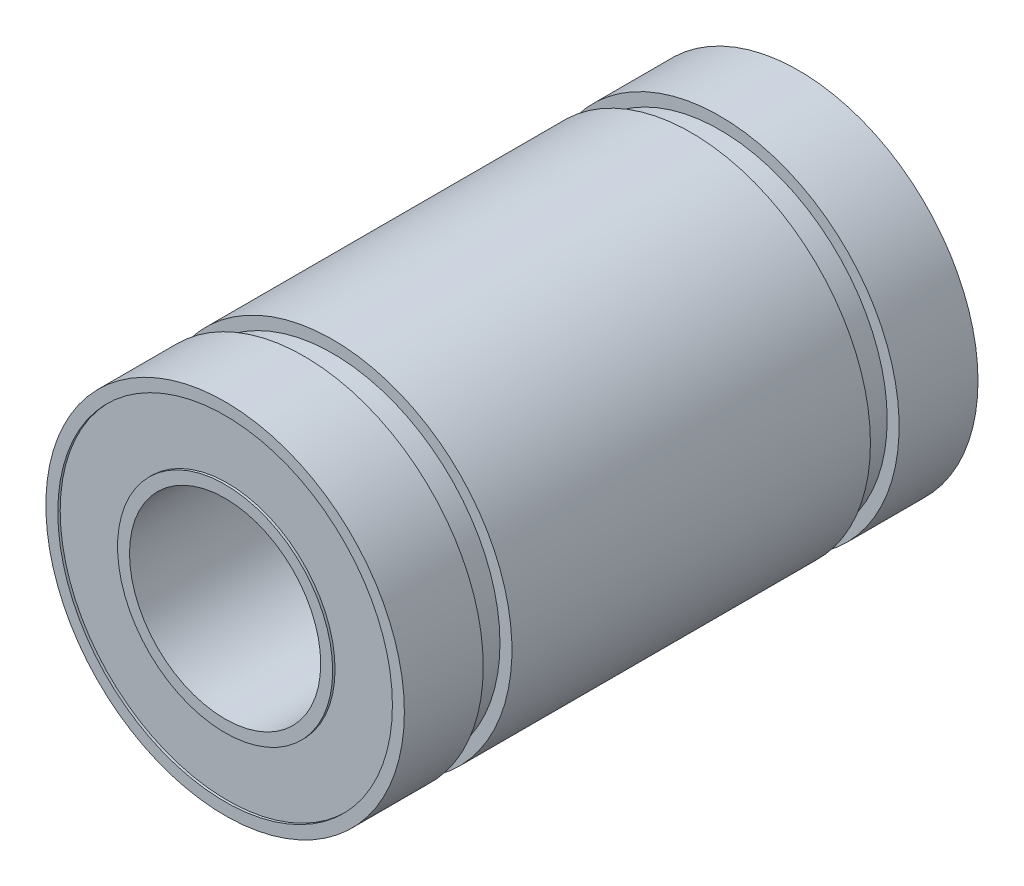
SolidWorks part; units mm, degrees
material "AISI 1020"
ref_plane "Plano frontal" through (0, 0, 0) normal (0, 0, 1) x (1, 0, 0)
ref_plane "Plano superior" through (0, 0, 0) normal (0, 1, 0) x (1, 0, 0)
ref_plane "Plano direito" through (0, 0, 0) normal (1, 0, 0) x (0, 0, -1)
sketch "Esboço1" plane through (0, 0, 0) normal (0, 0, 1) x (1, 0, 0)
  circle A0 centre (0, 0) radius 4
  circle A1 centre (0, 0) radius 7.5
  dimension "D1" = 8
  dimension "D2" = 15
extrude "Ressalto-extrusão1" add sketch "Esboço1" along normal mid plane 24
sketch "Esboço2" plane through (0, 0, 12) normal (0, 0, 1) x (1, 0, 0)
  circle A2 centre (0, 0) radius 7
  circle A3 centre (0, 0) radius 7
  circle A5 centre (0, 0) radius 4.5
  circle A6 centre (0, 0) radius 4.5
  dimension "D1" = 0.5
  dimension "D2" = 0.5
extrude "Corte-extrusão1" cut sketch "Esboço2" against normal blind 0.1
mirror "Espelhar1" about plane through (0, 0, 0) normal (0, 0, 1) of "Corte-extrusão1"
sketch "Esboço3" plane through (0, 0, 0) normal (1, 0, 0) x (0, 0, -1)
  line L0 (0, 0) -> (-12, 0) construction
  line L1 (-12, 7.5) -> (-12, -7.5) construction
  line L2 (12, 7.5) -> (-12, 7.5) construction
  line L3 (-8.7, 8) -> (-7.5, 8)
  line L4 (-8.7, 8) -> (-8.7, 7)
  line L5 (-8.7, 7) -> (-7.5, 7)
  line L6 (-7.5, 8) -> (-7.5, 7)
  line L7 (-8.7, 8) -> (-7.5, 7) construction
  line L8 (-8.7, 7) -> (-7.5, 8) construction
  line L9 (0, 0) -> (0, 7.5) construction
  line L10 (8.7, 7) -> (7.5, 8) construction
  line L11 (8.7, 8) -> (7.5, 7) construction
  line L12 (7.5, 8) -> (7.5, 7)
  line L13 (8.7, 7) -> (7.5, 7)
  line L14 (8.7, 8) -> (8.7, 7)
  line L15 (8.7, 8) -> (7.5, 8)
  point P5 (-8.1, 7.5)
  point P17 (8.1, 7.5)
  dimension "D1" = 15
  dimension "D2" = 14
  dimension "D3" = 1.2
revolve "Corte-Revolução1" cut sketch "Esboço3" angle 360 about L0
